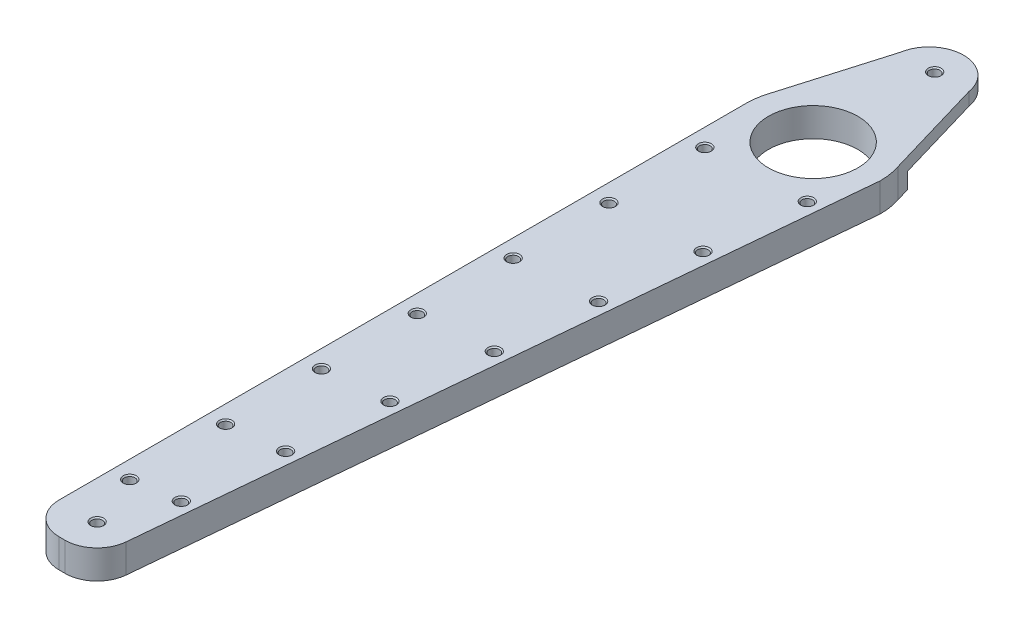
SolidWorks part; units mm, degrees
ref_plane "前视基准面" through (0, 0, 0) normal (0, 0, 1) x (1, 0, 0)
ref_plane "上视基准面" through (0, 0, 0) normal (0, 1, 0) x (1, 0, 0)
ref_plane "右视基准面" through (0, 0, 0) normal (1, 0, 0) x (0, 0, -1)
sketch "草图1" plane through (0, 0, 0) normal (0, 1, 0) x (1, 0, 0)
  line L0 (-21, 0) -> (-21, -215)
  line L1 (21, 0) -> (0.8466, -215.9293)
  line L2 (-11, -225) -> (-9.1101, -225)
  arc A0 (21, 0) -> (-21, 0) centre (0, 0) ccw
  arc A1 (-21, -215) -> (-11, -225) centre (-11, -215) ccw
  arc A2 (0.8466, -215.9293) -> (-9.1101, -225) centre (-9.1101, -215) cw
  dimension "D1" = 10
extrude "凸台-拉伸1" add sketch "草图1" along normal blind 15 contours L0 A1 L2 A2 L1 A0
sketch "草图2" plane through (0, 0, 0) normal (0, -1, 0) x (1, 0, 0)
  line L0 (0, 24.8705) -> (-8.6819, 198.279) construction
  line L1 (-6.4875, 24.5457) -> (-15.1695, 197.9542)
  line L2 (6.4875, 25.1953) -> (-2.1944, 198.6038)
  arc A0 (-6.4875, 24.5457) -> (6.4875, 25.1953) centre (0, 24.8705) ccw
  arc A1 (-2.1944, 198.6038) -> (-15.1695, 197.9542) centre (-8.6819, 198.279) ccw
  point P2 (-4.341, 111.5747)
extrude "切除-拉伸1" cut sketch "草图2" against normal blind 4
sketch "草图3" plane through (0, 0, 0) normal (0, -1, 0) x (-1, 0, 0)
  circle A0 centre (0, 0) radius 14
extrude "切除-拉伸2" cut sketch "草图3" against normal through all
sketch "草图7" plane through (0, 0, 0) normal (0, 1, 0) x (1, 0, 0)
  line L0 (-20.3523, 5.1751) -> (-10.6931, 38.0391)
  line L1 (20.3523, 5.1751) -> (10.6931, 38.0391)
  arc A0 (21, 0) -> (-21, 0) centre (0, 0) ccw construction
  arc A1 (10.6931, 38.0391) -> (-10.6931, 38.0391) centre (0, 36.2761) ccw
  arc A2 (20.3523, 5.1751) -> (-20.3523, 5.1751) centre (0, 0) ccw
extrude "凸台-拉伸4" add sketch "草图7" along normal blind 15 contours A2 L1 A1 L0
sketch "草图11" plane through (0, 0, 0) normal (1, 0, 0) x (0, 0, -1)
  line L12 (47.1135, 15) -> (38.0391, 15) construction
  line L13 (43.0391, 12.5) -> (60.0391, 12.5)
  line L14 (43.0391, 12.5) -> (43.0391, 2.5)
  line L15 (43.0391, 2.5) -> (60.0391, 2.5)
  line L16 (60.0391, 12.5) -> (60.0391, 2.5)
  line L17 (38.0391, 0) -> (47.1135, 0) construction
  line L18 (38.0391, 15) -> (38.0391, 0) construction
  dimension "D1" = 2.5
  dimension "D2" = 2.5
  dimension "D3" = 5
  dimension "D4" = 17
sketch "草图12" plane through (0, 0, 0) normal (1, 0, 0) x (0, 0, -1)
  line L0 (38.0391, 15) -> (38.0391, 0)
revolve "切除-旋转3" cut sketch "草图11" angle 360 about L0
sketch "草图14" plane through (0, 0, 0) normal (1, 0, 0) x (0, 0, -1)
  line L2 (22.2603, 12.5) -> (16.2603, 12.5)
  line L3 (22.2603, 12.5) -> (22.2603, 2.5)
  line L4 (22.2603, 2.5) -> (16.2603, 2.5)
  line L5 (16.2603, 12.5) -> (16.2603, 2.5)
  dimension "D1" = 6
sketch "草图15" plane through (0, 0, 0) normal (1, 0, 0) x (0, 0, -1)
  line L0 (0, 15) -> (0, 0)
revolve "切除-旋转4" cut sketch "草图14" angle 60 about L0 other way angle 90
sketch "草图16" plane through (20.1341, 0, -5.9177) normal (0.9594, 0, -0.282) x (-0.282, 0, -0.9594)
  line L0 (17.0339, 12.5) -> (17.0339, 2.5) construction
  line L1 (7.4244, 12.5) -> (17.0339, 12.5)
  line L2 (7.4244, 12.5) -> (7.4244, 2.5)
  line L3 (7.4244, 2.5) -> (17.0339, 2.5)
  line L4 (17.0339, 12.5) -> (17.0339, 2.5)
extrude "切除-拉伸4" cut sketch "草图16" against normal blind 5
sketch "草图17" plane through (-20.1341, 0, -5.9177) normal (-0.9594, 0, -0.282) x (-0.282, 0, 0.9594)
  line L1 (-17.0339, 12.5) -> (-7.4244, 12.5)
  line L2 (-17.0339, 12.5) -> (-17.0339, 2.5)
  line L3 (-17.0339, 2.5) -> (-7.4244, 2.5)
  line L4 (-7.4244, 12.5) -> (-7.4244, 2.5)
extrude "切除-拉伸5" cut sketch "草图17" against normal blind 5
sketch "草图20" plane through (0, 0, 0) normal (0, -1, 0) x (1, 0, 0)
  line L5 (21, 0) -> (0.8466, 215.9293)
  line L6 (-9.1101, 225) -> (-11, 225)
  line L7 (-21, 215) -> (-21, 0)
  line L8 (-19.9158, -6.6604) -> (-10.6931, -38.0391)
  line L9 (10.6931, -38.0391) -> (19.9158, -6.6604)
  line L10 (21, 0) -> (0.8466, 215.9293)
  line L11 (-9.1101, 225) -> (-11, 225)
  line L12 (-21, 215) -> (-21, 0)
  line L13 (-19.9158, -6.6604) -> (-10.6931, -38.0391)
  line L14 (10.6931, -38.0391) -> (19.9158, -6.6604)
  arc A5 (19.9158, -6.6604) -> (21, 0) centre (0, 0) ccw
  arc A6 (0.8466, 215.9293) -> (-9.1101, 225) centre (-9.1101, 215) ccw
  arc A7 (-11, 225) -> (-21, 215) centre (-11, 215) ccw
  arc A8 (-21, 0) -> (-19.9158, -6.6604) centre (0, 0) ccw
  arc A9 (-10.6931, -38.0391) -> (10.6931, -38.0391) centre (0, -36.2761) ccw
  arc A10 (19.9158, -6.6604) -> (21, 0) centre (0, 0) ccw
  arc A11 (0.8466, 215.9293) -> (-9.1101, 225) centre (-9.1101, 215) ccw
  arc A12 (-11, 225) -> (-21, 215) centre (-11, 215) ccw
  arc A13 (-21, 0) -> (-19.9158, -6.6604) centre (0, 0) ccw
  arc A14 (-10.6931, -38.0391) -> (10.6931, -38.0391) centre (0, -36.2761) ccw
  dimension "D1" = 0
extrude "切除-拉伸6" cut sketch "草图20" against normal blind 7.5
sketch "草图21" plane through (0, 7.5, 0) normal (0, -1, 0) x (1, 0, 0)
  line L6 (-21, 0) -> (-16.2603, 0)
  line L7 (14.0819, -8.1302) -> (18.7001, -10.7965)
  line L8 (18.7001, -10.7965) -> (19.9158, -6.6604)
  line L9 (21, 0) -> (0.8466, 215.9293)
  line L10 (-9.1101, 225) -> (-11, 225)
  line L11 (-21, 215) -> (-21, 0)
  line L12 (-21, 0) -> (-16.2603, 0)
  line L13 (14.0819, -8.1302) -> (18.7001, -10.7965)
  line L14 (18.7001, -10.7965) -> (19.9158, -6.6604)
  line L15 (21, 0) -> (0.8466, 215.9293)
  line L16 (-9.1101, 225) -> (-11, 225)
  line L17 (-21, 215) -> (-21, 0)
  circle A0 centre (0, 0) radius 14 construction
  circle A1 centre (0, -38.0391) radius 5
  circle A2 centre (0, -38.0391) radius 5
  circle A3 centre (0, 0) radius 14
  arc A6 (-16.2603, 0) -> (-2.0308, -16.133) centre (0, 0) ccw
  arc A7 (2.0308, -16.133) -> (-2.0308, -16.133) centre (0, -38.0391) ccw
  arc A8 (2.0308, -16.133) -> (14.0819, -8.1302) centre (0, 0) ccw
  arc A9 (19.9158, -6.6604) -> (21, 0) centre (0, 0) ccw
  arc A10 (0.8466, 215.9293) -> (-9.1101, 225) centre (-9.1101, 215) ccw
  arc A11 (-11, 225) -> (-21, 215) centre (-11, 215) ccw
  arc A12 (-16.2603, 0) -> (-2.0308, -16.133) centre (0, 0) ccw
  arc A13 (2.0308, -16.133) -> (-2.0308, -16.133) centre (0, -38.0391) ccw
  arc A14 (2.0308, -16.133) -> (14.0819, -8.1302) centre (0, 0) ccw
  arc A15 (19.9158, -6.6604) -> (21, 0) centre (0, 0) ccw
  arc A16 (0.8466, 215.9293) -> (-9.1101, 225) centre (-9.1101, 215) ccw
  arc A17 (-11, 225) -> (-21, 215) centre (-11, 215) ccw
  dimension "D1" = 0
  dimension "D2" = 0
sketch "草图22" plane through (0, 12.5, 0) normal (0, -1, 0) x (1, 0, 0)
  line L4 (-19.9158, -6.6604) -> (-10.6931, -38.0391)
  line L5 (10.6931, -38.0391) -> (18.7001, -10.7965)
  line L6 (18.7001, -10.7965) -> (14.0819, -8.1302)
  line L7 (-16.2603, 0) -> (-21, 0)
  line L8 (-19.9158, -6.6604) -> (-10.6931, -38.0391)
  line L9 (10.6931, -38.0391) -> (18.7001, -10.7965)
  line L10 (18.7001, -10.7965) -> (14.0819, -8.1302)
  line L11 (-16.2603, 0) -> (-21, 0)
  arc A5 (-21, 0) -> (-19.9158, -6.6604) centre (0, 0) ccw
  arc A6 (-10.6931, -38.0391) -> (10.6931, -38.0391) centre (0, -36.2761) ccw
  arc A7 (2.0308, -16.133) -> (14.0819, -8.1302) centre (0, 0) ccw
  arc A8 (2.0308, -16.133) -> (-2.0308, -16.133) centre (0, -38.0391) ccw
  arc A9 (-16.2603, 0) -> (-2.0308, -16.133) centre (0, 0) ccw
  arc A10 (-21, 0) -> (-19.9158, -6.6604) centre (0, 0) ccw
  arc A11 (-10.6931, -38.0391) -> (10.6931, -38.0391) centre (0, -36.2761) ccw
  arc A12 (2.0308, -16.133) -> (14.0819, -8.1302) centre (0, 0) ccw
  arc A13 (2.0308, -16.133) -> (-2.0308, -16.133) centre (0, -38.0391) ccw
  arc A14 (-16.2603, 0) -> (-2.0308, -16.133) centre (0, 0) ccw
  dimension "D1" = 0
extrude "凸台-拉伸6" add sketch "草图22" along normal blind 1.5
extrude "凸台-拉伸7" add sketch "草图21" along normal blind 1.5
sketch "草图23" plane through (0, 15, 0) normal (0, 1, 0) x (1, 0, 0)
  point P0 (-4.3384, -226.0968) [skipped]
  point P2 (-9.1101, -215)
  point P3 (15.1767, -17.0055)
  point P4 (0, 38.0391)
  point P8 (-15.5, -18.3981)
  point P9 (-15.5, -48.3981)
  point P10 (-15.5, -78.3981)
  point P11 (-15.5, -108.3981)
  point P12 (-15.5, -138.3981)
  point P13 (-15.5, -168.3981)
  point P14 (-15.5, -198.3981)
  point P17 (12.3889, -46.8757)
  point P18 (9.601, -76.7459)
  point P21 (6.8131, -106.616)
  point P22 (4.0252, -136.4862)
  point P23 (1.2373, -166.3564)
  point P24 (-1.5506, -196.2266)
  dimension "D1" = 7
  dimension "D5" = 8
hole_wizard "M4 螺纹孔1" positions "草图23" profile "草图24" tap size "M4" standard "DIN" end condition up to next
sketch "草图24" plane through (-1.5506, 15, 196.2266) normal (1, 0, 0) x (0, 0, 1)
  line L0 (0, 0) -> (0, 9)
  line L1 (0, 9) -> (1.65, 9)
  line L2 (1.65, 9) -> (1.65, 0.375)
  line L3 (1.65, 0.375) -> (2.025, 0)
  line L5 (2.025, 0) -> (0, 0)
  line L6 (-1.65, 0.375) -> (-2.025, 0) construction
  line L11 (0, -6.35) -> (0, 107.95) construction
  dimension "通孔螺纹孔钻头直径" = 3.3
  dimension "通孔螺纹孔钻头深度" = 9
  dimension "近端锥形沉头孔直径" = 4.05
  dimension "近端锥形沉头孔角度" = 90
cosmetic thread "孔螺纹线1" parameters "D2"=4
cosmetic thread "孔螺纹线2" parameters "D2"=4
cosmetic thread "孔螺纹线3" parameters "D2"=4
cosmetic thread "孔螺纹线4" parameters "D2"=4
cosmetic thread "孔螺纹线5" parameters "D2"=4
cosmetic thread "孔螺纹线6" parameters "D2"=4
cosmetic thread "孔螺纹线7" parameters "D2"=4
cosmetic thread "孔螺纹线8" parameters "D2"=4
cosmetic thread "孔螺纹线9" parameters "D2"=4
cosmetic thread "孔螺纹线10" parameters "D2"=4
cosmetic thread "孔螺纹线11" parameters "D2"=4
cosmetic thread "孔螺纹线12" parameters "D2"=4
cosmetic thread "孔螺纹线13" parameters "D2"=4
cosmetic thread "孔螺纹线14" parameters "D2"=4
cosmetic thread "孔螺纹线15" parameters "D2"=4
cosmetic thread "孔螺纹线16" parameters "D2"=4
